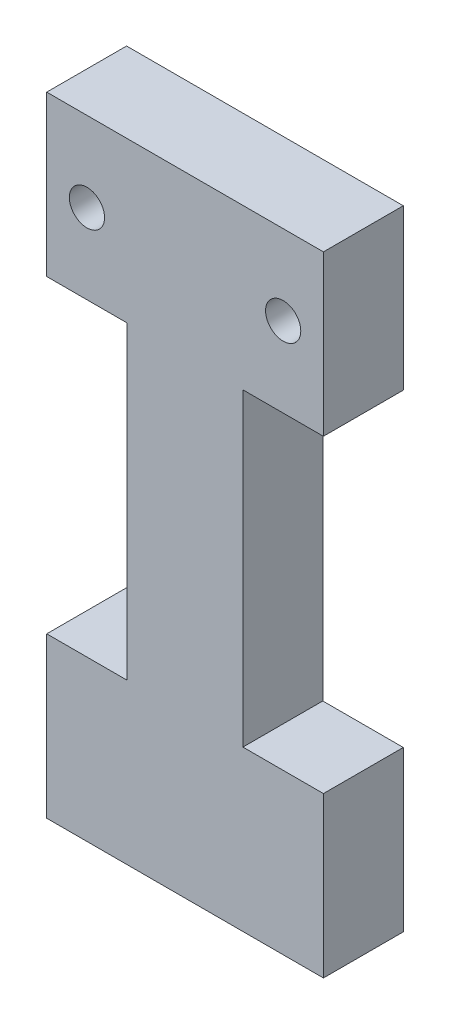
SolidWorks part; units mm, degrees
ref_plane "Front Plane" through (0, 0, 0) normal (0, 0, 1) x (1, 0, 0)
ref_plane "Top Plane" through (0, 0, 0) normal (0, 1, 0) x (1, 0, 0)
ref_plane "Right Plane" through (0, 0, 0) normal (1, 0, 0) x (0, 0, -1)
sketch "Sketch1" plane through (0, 0, 0) normal (0, 0, 1) x (1, 0, 0)
  line L1 (4.6, -25) -> (-4.6, -25)
  line L2 (4.6, -25) -> (4.6, 25)
  line L3 (4.6, 25) -> (-4.6, 25)
  line L4 (-4.6, -25) -> (-4.6, 25)
  line L5 (4.6, -25) -> (-4.6, 25) construction
  line L6 (4.6, 25) -> (-4.6, -25) construction
  line L7 (-4.6, 25) -> (-11, 25)
  line L9 (-4.6, 12.3) -> (-11, 12.3)
  line L10 (-11, 25) -> (-11, 12.3)
  line L11 (4.6, 25) -> (11, 25)
  line L13 (4.6, 12.3) -> (11, 12.3)
  line L14 (11, 25) -> (11, 12.3)
  line L15 (4.6, -25) -> (11, -25)
  line L17 (4.6, -12.3) -> (11, -12.3)
  line L18 (11, -25) -> (11, -12.3)
  line L19 (-4.6, -25) -> (-11, -25)
  line L21 (-4.6, -12.3) -> (-11, -12.3)
  line L22 (-11, -25) -> (-11, -12.3)
  circle A1 centre (-7.8, 18.65) radius 1.4
  circle A2 centre (7.8, 18.65) radius 1.4
  point P0 (0, 0)
  point P20 (-7.8, 25)
  point P21 (7.8, 25)
  point P22 (-11, 18.65)
  point P23 (-11, -18.65)
  dimension "D7" = 2.8
  dimension "D1" = 50
  dimension "D2" = 12.7
  dimension "D3" = 22
  dimension "D4" = 6.4
extrude "Boss-Extrude1" add sketch "Sketch1" along normal blind 6.35
sketch "Sketch2" plane through (0, 0, 6.35) normal (0, 0, 1) x (1, 0, 0)
  line L1 (-11, -25) -> (11, -25) construction
  circle A0 centre (0, -20) radius 0.7
  dimension "D1" = 1.4
  dimension "D2" = 5
extrude "Cut-Extrude1" [suppressed] cut sketch "Sketch2" against normal through all
